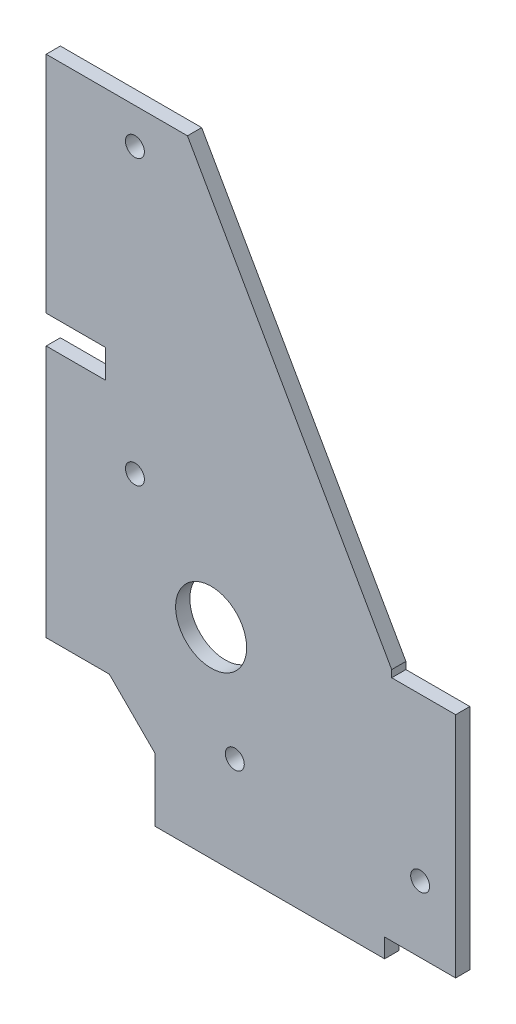
SolidWorks part; units mm, degrees
ref_plane "Front Plane" through (0, 0, 0) normal (0, 0, 1) x (1, 0, 0)
ref_plane "Top Plane" through (0, 0, 0) normal (0, 1, 0) x (1, 0, 0)
ref_plane "Right Plane" through (0, 0, 0) normal (1, 0, 0) x (0, 0, -1)
sketch "Sketch1" plane through (0, 0, 0) normal (0, 0, 1) x (1, 0, 0)
  line L0 (0, 0) -> (143.3, 0)
  line L2 (0, 259.8) -> (0, 0)
  line L4 (173.3, 60) -> (173.3, 8.3)
  line L5 (0, 259.8) -> (60, 259.8)
  line L6 (60, 259.8) -> (173.3, 60)
  line L10 (173.3, 8.3) -> (143.3, 8.3)
  line L11 (143.3, 0) -> (143.3, 8.3)
  dimension "D1" = 60
  dimension "D2" = 259.8
  dimension "D3" = 173.3
  dimension "D4" = 60
  dimension "D5" = 8.3
  dimension "D6" = 30
extrude "Boss-Extrude1" add sketch "Sketch1" along normal blind 6
sketch "Sketch2" plane through (0, 0, 6) normal (0, 0, 1) x (1, 0, 0)
  line L0 (46.3, 0) -> (46.3, 19)
  line L1 (0, 0) -> (143.3, 0) construction
  line L2 (46.3, 19) -> (19, 46.3)
  line L3 (19, 46.3) -> (0, 46.3)
  line L4 (0, 259.8) -> (0, 0) construction
  line L5 (0, 46.3) -> (0, 0)
  line L6 (0, 0) -> (46.3, 0)
  line L7 (143.3, 8.3) -> (173.3, 8.3) construction
  line L8 (173.3, 8.3) -> (173.3, 60) construction
  line L9 (60, 259.8) -> (0, 259.8) construction
  circle A0 centre (158.3, 36.3) radius 4
  circle A1 centre (37.8, 244.8) radius 4
  circle A2 centre (37.8, 125) radius 4
  circle A3 centre (80, 43.8) radius 4
  circle A4 centre (70, 85) radius 15
  dimension "D6" = 8
  dimension "D12" = 30
  dimension "D1" = 46.3
  dimension "D2" = 46.3
  dimension "D3" = 19
  dimension "D4" = 19
  dimension "D5" = 28
  dimension "D7" = 15
  dimension "D8" = 15
  dimension "D9" = 37.8
  dimension "D10" = 43.8
  dimension "D11" = 125
  dimension "D13" = 85
  dimension "D14" = 70
  dimension "D15" = 80
extrude "Cut-Extrude1" cut sketch "Sketch2" against normal through all
sketch "Croquis2" plane through (0, 0, 6) normal (0, 0, 1) x (1, 0, 0)
  line L0 (46.3, 0) -> (46.3, 19) construction
  line L1 (143.3, 0) -> (46.3, 0)
  line L2 (143.3, 0) -> (143.3, 0.3)
  line L3 (143.3, 0.3) -> (46.3, 0.3)
  line L4 (46.3, 0) -> (46.3, 0.3)
extrude "Cortar-Extruir1" cut sketch "Croquis2" against normal blind 10
sketch "Croquis3" plane through (0, 0, 6) normal (0, 0, 1) x (1, 0, 0)
  line L0 (46.3, 19) -> (19, 46.3)
  line L1 (19, 46.3) -> (27, 46.3)
  line L2 (46.3, 19) -> (46.3, 27)
  line L3 (46.3, 27) -> (27, 46.3)
extrude "Cortar-Extruir2" cut sketch "Croquis3" against normal blind 10
sketch "Croquis4" plane through (0, 0, 6) normal (0, 0, 1) x (1, 0, 0)
  line L0 (143.3, 8.3) -> (46.3, 8.3) construction
  line L1 (46.3, 0.3) -> (46.3, 27) construction
  circle A0 centre (80, 43.8) radius 4
  circle A1 centre (80, 36.3) radius 4
  circle A2 centre (158.3, 36.3) radius 4 construction
  circle M11 centre (80, 43.8) radius 4
  dimension "D1" = 0
extrude "Cortar-Extruir3" cut sketch "Croquis4" against normal blind 6 contours A1 M11
sketch "Croquis6" plane through (0, 0, 6) normal (0, 0, 1) x (1, 0, 0)
  circle A0 centre (80, 43.8) radius 4
  circle A1 centre (80, 36.3) radius 4
  arc M3 (78.6081, 40.05) -> (81.3919, 40.05) centre (80, 43.8) cw
extrude "Saliente-Extruir2" add sketch "Croquis6" against normal blind 6 contours A1 M3
sketch "Croquis7" plane through (0, 0, 6) normal (0, 0, 1) x (1, 0, 0)
  line L1 (0, 259.8) -> (0.3, 259.8)
  line L2 (0, 259.8) -> (0, 37.75)
  line L3 (0, 37.75) -> (0.3, 37.75)
  line L4 (0.3, 259.8) -> (0.3, 37.75)
extrude "Cortar-Extruir4" cut sketch "Croquis7" against normal blind 6
sketch "Croquis8" plane through (0, 0, 6) normal (0, 0, 1) x (1, 0, 0)
  line L0 (0.3, 153.05) -> (25.3, 153.05)
  line L1 (0.3, 46.3) -> (0.3, 259.8) construction
  line L2 (25.3, 153.05) -> (25.3, 165.05)
  line L3 (25.3, 165.05) -> (0.3, 165.05)
  line L4 (0.3, 153.05) -> (0.3, 165.05)
  dimension "D1" = 25
extrude "Cortar-Extruir5" cut sketch "Croquis8" against normal blind 6
sketch "Croquis9" plane through (0, 0, 6) normal (0, 0, 1) x (1, 0, 0)
  line L0 (173.3, 60) -> (173.3, 104.64)
  line L1 (143.3, 8.3) -> (173.3, 8.3) construction
  line L2 (173.3, 104.64) -> (147.9861, 104.64)
  line L3 (173.3, 60) -> (60, 259.8) construction
  line L4 (147.9861, 104.64) -> (147.9861, 107.64) construction
  line L5 (147.9861, 107.64) -> (146.2849, 107.64) construction
  line L6 (146.2849, 107.64) -> (146.2849, 104.64)
  line L7 (146.2849, 104.64) -> (147.9861, 104.64)
  line L8 (146.2849, 104.64) -> (146.2849, 60)
  line L9 (146.2849, 60) -> (173.3, 60)
  line M12 (173.3, 60) -> (60, 259.8)
  dimension "D1" = 96.34
extrude "Saliente-Extruir3" add sketch "Croquis9" along normal blind 10 separate body contours L0 L2 M12
sketch "Croquis10" plane through (0, 0, 6) normal (0, 0, 1) x (1, 0, 0)
  line L0 (147.9861, 104.64) -> (146.2861, 104.64)
  line L1 (146.2861, 104.64) -> (146.2861, 107.6379)
  line L2 (173.3, 60) -> (60, 259.8) construction
  line L3 (146.2861, 107.6379) -> (147.9861, 104.64)
extrude "Cortar-Extruir6" cut sketch "Croquis10" against normal blind 10
sketch "Croquis11" plane through (0, 0, 16) normal (0, 0, 1) x (1, 0, 0)
  line L0 (173.3, 60) -> (173.3, 104.64)
  line L1 (173.3, 104.64) -> (147.9861, 104.64)
  line L2 (147.9861, 104.64) -> (173.3, 60)
extrude "Saliente-Extruir4" add sketch "Croquis11" against normal blind 16
sketch "Croquis12" plane through (0, 104.64, 0) normal (0, 1, 0) x (1, 0, 0)
  line L1 (147.9861, -6) -> (173.3, -6)
  line L2 (147.9861, -6) -> (147.9861, -16)
  line L3 (147.9861, -16) -> (173.3, -16)
  line L4 (173.3, -6) -> (173.3, -16)
extrude "Cortar-Extruir7" cut sketch "Croquis12" against normal blind 67
sketch "Croquis13" plane through (0, 0, 6) normal (0, 0, 1) x (1, 0, 0)
  circle A0 centre (80, 41.8) radius 4
  circle A1 centre (80, 36.3) radius 4 construction
  dimension "D1" = 0
  dimension "D2" = 5.5
extrude "Cortar-Extruir8" cut sketch "Croquis13" against normal blind 10
sketch "Croquis14" plane through (0, 0, 6) normal (0, 0, 1) x (1, 0, 0)
  circle A0 centre (80, 41.8) radius 4
  circle A1 centre (80, 36.3) radius 4
  arc M2 (82.9047, 39.05) -> (77.0953, 39.05) centre (80, 36.3) cw
extrude "Saliente-Extruir5" add sketch "Croquis14" against normal blind 6 contours A0 M2
sketch "Croquis15" plane through (0, 0, 6) normal (0, 0, 1) x (1, 0, 0)
  circle A0 centre (80, 47.3) radius 4
  circle A1 centre (80, 41.8) radius 4 construction
  dimension "D1" = 5.5
extrude "Cortar-Extruir9" cut sketch "Croquis15" against normal blind 10
sketch "Croquis16" plane through (0, 0, 6) normal (0, 0, 1) x (1, 0, 0)
  circle A0 centre (80, 41.8) radius 4
  circle A1 centre (80, 47.3) radius 4
  arc M2 (82.9047, 44.55) -> (77.0953, 44.55) centre (80, 41.8) cw
extrude "Saliente-Extruir7" add sketch "Croquis16" against normal blind 6 contours A1 M2
sketch "Croquis18" plane through (0, 0, 6) normal (0, 0, 1) x (1, 0, 0)
  circle A0 centre (80, 41.8) radius 4
  circle A1 centre (80, 47.3) radius 4 construction
  dimension "D1" = 5.5
extrude "Cortar-Extruir10" cut sketch "Croquis18" against normal blind 6
sketch "Croquis19" plane through (0, 0, 6) normal (0, 0, 1) x (1, 0, 0)
  circle A0 centre (80, 47.3) radius 4
  circle A1 centre (80, 41.8) radius 4
  arc M3 (77.0953, 44.55) -> (82.9047, 44.55) centre (80, 47.3) cw
extrude "Saliente-Extruir8" add sketch "Croquis19" against normal blind 6 contours A1 M3
